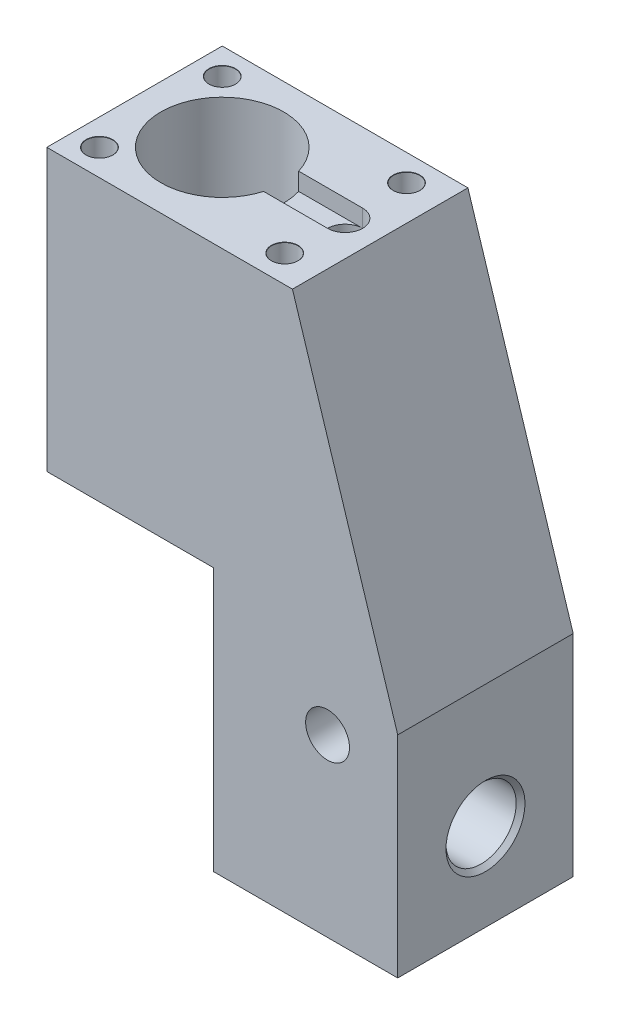
SolidWorks part; units mm, degrees
ref_plane "Front Plane" through (0, 0, 0) normal (0, 0, 1) x (1, 0, 0)
ref_plane "Top Plane" through (0, 0, 0) normal (0, 1, 0) x (1, 0, 0)
ref_plane "Right Plane" through (0, 0, 0) normal (1, 0, 0) x (0, 0, -1)
sketch "Sketch1" plane through (0, 0, 0) normal (0, 0, 1) x (1, 0, 0)
  line L0 (0, 0) -> (28, 0)
  line L2 (0, 0) -> (0, -32)
  line L4 (40, -38) -> (40, -62)
  line L5 (28, 0) -> (40, -38)
  line L6 (19, -62) -> (40, -62)
  line L7 (0, -32) -> (19, -32)
  line L9 (19, -62) -> (19, -32) construction
  line L12 (19, -32) -> (19, -62)
  dimension "D2" = 21
extrude "Boss-Extrude1" add sketch "Sketch1" along normal mid plane 20
sketch "Sketch2" plane through (0, 0, 0) normal (0, 1, 0) x (1, 0, 0)
  circle A0 centre (10, 0) radius 7
  dimension "D2" = 14
extrude "Cut-Extrude1" cut sketch "Sketch2" against normal up to next
sketch "Sketch5" plane through (40, 0, 0) normal (1, 0, 0) x (0, 0, -1)
  line L0 (0, -62) -> (0, -52) construction
  line L1 (-10, -62) -> (10, -62) construction
  circle A0 centre (0, -52) radius 4
  dimension "D2" = 8
  dimension "D1" = 10
extrude "Cut-Extrude2" cut sketch "Sketch5" against normal up to next
chamfer "Chamfer1" distance 0.5 angle 45 1 edges at (40, -52, -4)
sketch "Sketch6" plane through (0, -62, 0) normal (0, -1, 0) x (1, 0, 0)
  line L0 (40, 0) -> (32, 0) construction
  line L1 (40, 10) -> (40, -10) construction
  line L2 (32, 0) -> (24, 0) construction
  circle A0 centre (32, 0) radius 2
  circle A1 centre (23.8856, 0) radius 2
  circle A2 centre (32, 0) radius 1
  dimension "D3" = 4
  dimension "D4" = 2
  dimension "D1" = 8
  dimension "D2" = 8
sketch "Sketch7" plane through (0, -62, 0) normal (0, -1, 0) x (-1, 0, 0)
sketch "Sketch9" plane through (0, -62, 0) normal (0, -1, 0) x (-1, 0, 0)
sketch "Sketch10" plane through (0, -62, 0) normal (0, -1, 0) x (-1, 0, 0)
sketch "Sketch12" plane through (0, -62, 0) normal (0, -1, 0) x (-1, 0, 0)
sketch "Sketch14" plane through (0, -62, 0) normal (0, -1, 0) x (-1, 0, 0)
  point P0 (-32, 0)
  point P3 (-24, 0)
hole_wizard "Ø4.2 (4.2) Diameter Hole1" positions "Sketch14" profile "Sketch13" hole size "Ø4.2" standard "ANSI Metric"
sketch "Sketch13" plane through (32, -62, 0) normal (1, 0, 0) x (0, 0, -1)
  line L0 (0, 0) -> (0, 9.2618)
  line L1 (0, 9.2618) -> (2.1, 8)
  line L2 (2.1, 8) -> (2.1, 0.025)
  line L3 (2.1, 0.025) -> (2.125, 0)
  line L5 (2.125, 0) -> (0, 0)
  line L6 (-2.1, 0.025) -> (-2.125, 0) construction
  line L10 (0, 9.2618) -> (-2.1, 8) construction
  line L11 (0, -6.35) -> (0, 107.95) construction
  dimension "Hole Dia." = 4.2
  dimension "Hole Depth" = 8
  dimension "Near C'Sink Dia." = 4.25
  dimension "Near C'Sink Angle" = 90
  dimension "Drill Angle" = 118
cosmetic thread "Cosmetic Thread1" parameters "D2"=5
cosmetic thread "Cosmetic Thread2" parameters "D2"=5
sketch "Sketch15" plane through (0, 0, 10) normal (0, 0, 1) x (1, 0, 0)
  circle A1 centre (32, -42) radius 2.5
  dimension "D2" = 5
extrude "Cut-Extrude4" cut sketch "Sketch15" against normal up to next
extrude "Cut-Extrude6" cut sketch "Sketch6" against normal blind 21 contours A2
sketch "Sketch22" plane through (0, 0, 0) normal (0, 1, 0) x (1, 0, 0)
  line L0 (0, 0) -> (24, 0) construction
  line L2 (24, 2) -> (16.7082, 2)
  line L3 (24, -2) -> (16.7082, -2)
  circle A0 centre (24, 0) radius 2
  circle A1 centre (10, 0) radius 7 construction
  dimension "D1" = 24
  dimension "D2" = 4
extrude "Cut-Extrude10" cut sketch "Sketch22" against normal blind 2
sketch "Sketch23" plane through (0, 0, 0) normal (0, 1, 0) x (1, 0, 0)
  circle A0 centre (24, 0) radius 1.9983
extrude "Cut-Extrude11" cut sketch "Sketch23" against normal blind 30
sketch "Sketch24" plane through (0, 0, 0) normal (0, 1, 0) x (1, 0, 0)
  circle A0 centre (24, 0) radius 1
  dimension "D1" = 2
extrude "Cut-Extrude12" cut sketch "Sketch24" against normal blind 51
sketch "Sketch25" plane through (0, 0, 0) normal (0, 1, 0) x (1, 0, 0)
  line L0 (0, -10) -> (0, 10) construction
  line L1 (0, 0) -> (0, 7) construction
  line L2 (0, 7) -> (3, 7) construction
  line L3 (0, 0) -> (0, -7) construction
  circle A0 centre (3, 7) radius 1.5
  circle A1 centre (24, 7) radius 1.5
  circle A2 centre (24, -6.8803) radius 1.5
  circle A4 centre (3, -7) radius 1.5
  dimension "D1" = 3
  dimension "D6" = 3
  dimension "D2" = 24
  dimension "D3" = 3
  dimension "D4" = 7
  dimension "D5" = 7
sketch "Sketch26" plane through (0, 0, 0) normal (0, 1, 0) x (1, 0, 0)
  point P0 (24, 7)
  point P3 (24, -6.8803)
  point P6 (3, -7)
  point P9 (3, 7)
hole_wizard "Ø3.0 (3) Diameter Hole2" positions "Sketch26" profile "Sketch27" hole size "Ø3.0" standard "ANSI Metric"
sketch "Sketch27" plane through (24, 0, -7) normal (1, 0, 0) x (0, 0, 1)
  line L0 (0, 0) -> (0, 9)
  line L1 (0, 9) -> (1.5, 8.0987)
  line L2 (1.5, 8.0987) -> (1.5, 0.025)
  line L3 (1.5, 0.025) -> (1.525, 0)
  line L5 (1.525, 0) -> (0, 0)
  line L6 (-1.5, 0.025) -> (-1.525, 0) construction
  line L10 (0, 9) -> (-1.5, 8.0987) construction
  line L11 (0, -6.35) -> (0, 107.95) construction
  dimension "Hole Dia." = 3
  dimension "Hole Depth" = 9
  dimension "Near C'Sink Dia." = 3.05
  dimension "Near C'Sink Angle" = 90
  dimension "Drill Angle" = 118
cosmetic thread "Cosmetic Thread3" parameters "D2"=4
cosmetic thread "Cosmetic Thread4" parameters "D2"=4
cosmetic thread "Cosmetic Thread5" parameters "D2"=4
cosmetic thread "Cosmetic Thread6" parameters "D2"=4
sketch "Sketch28" plane through (0, 0, 0) normal (-1, 0, 0) x (0, 0, 1)
  circle A0 centre (-3, -17) radius 1.6
  circle A2 centre (3, -17.201) radius 1.6
  dimension "D1" = 17
  dimension "D2" = 3.2
  dimension "D4" = 3.2
extrude "Cut-Extrude13" cut sketch "Sketch28" against normal up to next
